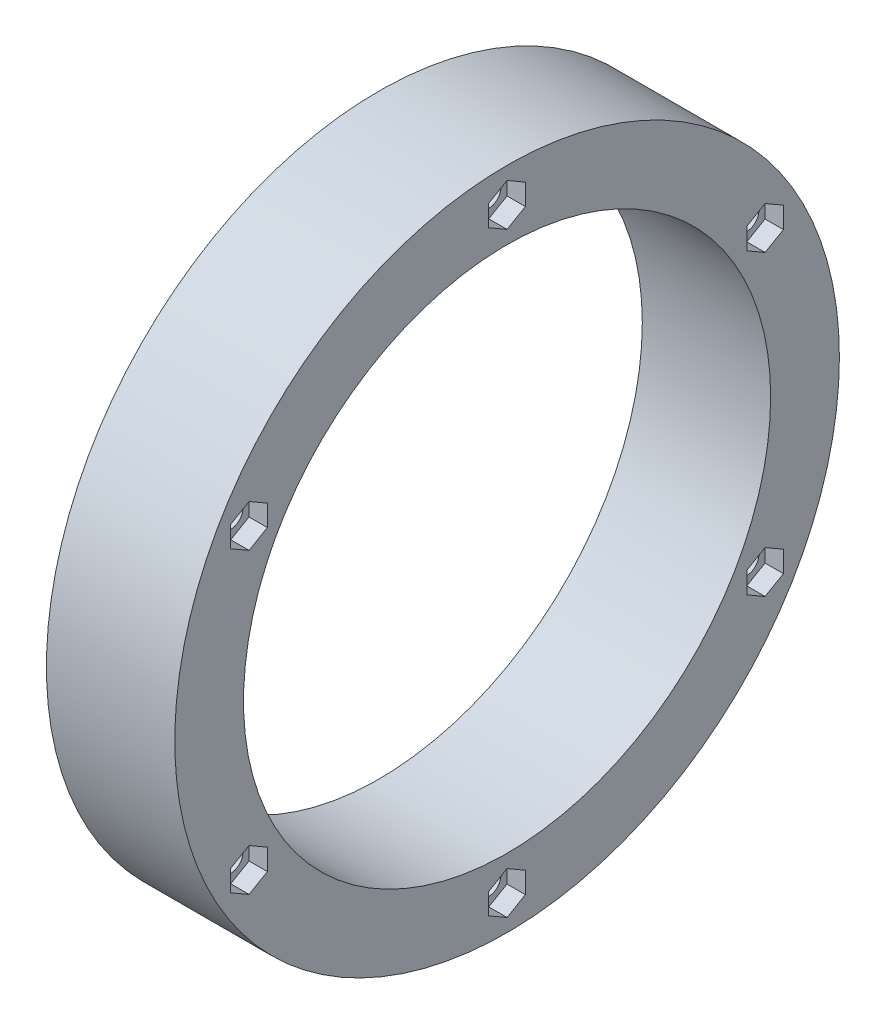
SolidWorks part; units mm, degrees
ref_plane "Front Plane" through (0, 0, 0) normal (0, 0, 1) x (1, 0, 0)
ref_plane "Top Plane" through (0, 0, 0) normal (0, 1, 0) x (1, 0, 0)
ref_plane "Right Plane" through (0, 0, 0) normal (1, 0, 0) x (0, 0, -1)
sketch "Sketch1" plane through (0, 0, 0) normal (1, 0, 0) x (0, 0, -1)
  circle A0 centre (0, 0) radius 72.5
  circle A1 centre (0, 0) radius 57.5
  dimension "D1" = 145
  dimension "D2" = 15
extrude "Boss-Extrude1" add sketch "Sketch1" along normal blind 28
sketch "Sketch2" plane through (28, 0, 0) normal (1, 0, 0) x (0, 0, -1)
  line L0 (52.2917, 30.1906) -> (56.2917, 27.8812)
  line L1 (0, 60.3812) -> (4, 62.6906)
  line L2 (4, 62.6906) -> (4, 67.3094)
  line L3 (4, 67.3094) -> (0, 69.6188)
  line L4 (0, 69.6188) -> (-4, 67.3094)
  line L5 (-4, 67.3094) -> (-4, 62.6906)
  line L6 (-4, 62.6906) -> (0, 60.3812)
  line L7 (56.2917, 27.8812) -> (60.2917, 30.1906)
  line L8 (60.2917, 30.1906) -> (60.2917, 34.8094)
  line L9 (60.2917, 34.8094) -> (56.2917, 37.1188)
  line L10 (56.2917, 37.1188) -> (52.2917, 34.8094)
  line L11 (52.2917, 34.8094) -> (52.2917, 30.1906)
  line L12 (52.2917, -30.1906) -> (52.2917, -34.8094)
  line L13 (52.2917, -34.8094) -> (56.2917, -37.1188)
  line L14 (56.2917, -37.1188) -> (60.2917, -34.8094)
  line L15 (60.2917, -34.8094) -> (60.2917, -30.1906)
  line L16 (60.2917, -30.1906) -> (56.2917, -27.8812)
  line L17 (56.2917, -27.8812) -> (52.2917, -30.1906)
  line L18 (0, -60.3812) -> (-4, -62.6906)
  line L19 (-4, -62.6906) -> (-4, -67.3094)
  line L20 (-4, -67.3094) -> (0, -69.6188)
  line L21 (0, -69.6188) -> (4, -67.3094)
  line L22 (4, -67.3094) -> (4, -62.6906)
  line L23 (4, -62.6906) -> (0, -60.3812)
  line L24 (-52.2917, -30.1906) -> (-56.2917, -27.8812)
  line L25 (-56.2917, -27.8812) -> (-60.2917, -30.1906)
  line L26 (-60.2917, -30.1906) -> (-60.2917, -34.8094)
  line L27 (-60.2917, -34.8094) -> (-56.2917, -37.1188)
  line L28 (-56.2917, -37.1188) -> (-52.2917, -34.8094)
  line L29 (-52.2917, -34.8094) -> (-52.2917, -30.1906)
  line L30 (-52.2917, 30.1906) -> (-52.2917, 34.8094)
  line L31 (-52.2917, 34.8094) -> (-56.2917, 37.1188)
  line L32 (-56.2917, 37.1188) -> (-60.2917, 34.8094)
  line L33 (-60.2917, 34.8094) -> (-60.2917, 30.1906)
  line L34 (-60.2917, 30.1906) -> (-56.2917, 27.8812)
  line L35 (-56.2917, 27.8812) -> (-52.2917, 30.1906)
  circle A0 centre (0, 65) radius 4 construction
  circle A1 centre (56.2917, 32.5) radius 4 construction
  circle A2 centre (56.2917, -32.5) radius 4 construction
  circle A3 centre (0, -65) radius 4 construction
  circle A4 centre (-56.2917, -32.5) radius 4 construction
  circle A5 centre (-56.2917, 32.5) radius 4 construction
  point P52 (0, 0)
  dimension "D1" = 8
  dimension "D2" = 65
  dimension "D3" = 6
extrude "Cut-Extrude1" cut sketch "Sketch2" against normal blind 4
sketch "Sketch3" plane through (28, 0, 0) normal (1, 0, 0) x (0, 0, -1)
  line L0 (0, 69.6188) -> (0, 60.3812) construction
  circle A0 centre (0, 65) radius 2.65
  circle A1 centre (56.2917, 32.5) radius 2.65
  circle A2 centre (56.2917, -32.5) radius 2.65
  circle A3 centre (0, -65) radius 2.65
  circle A4 centre (-56.2917, -32.5) radius 2.65
  circle A5 centre (-56.2917, 32.5) radius 2.65
  point P3 (0, 65)
  point P20 (0, 0)
  dimension "D1" = 5.3
  dimension "D2" = 6
extrude "Cut-Extrude2" cut sketch "Sketch3" against normal up to next
